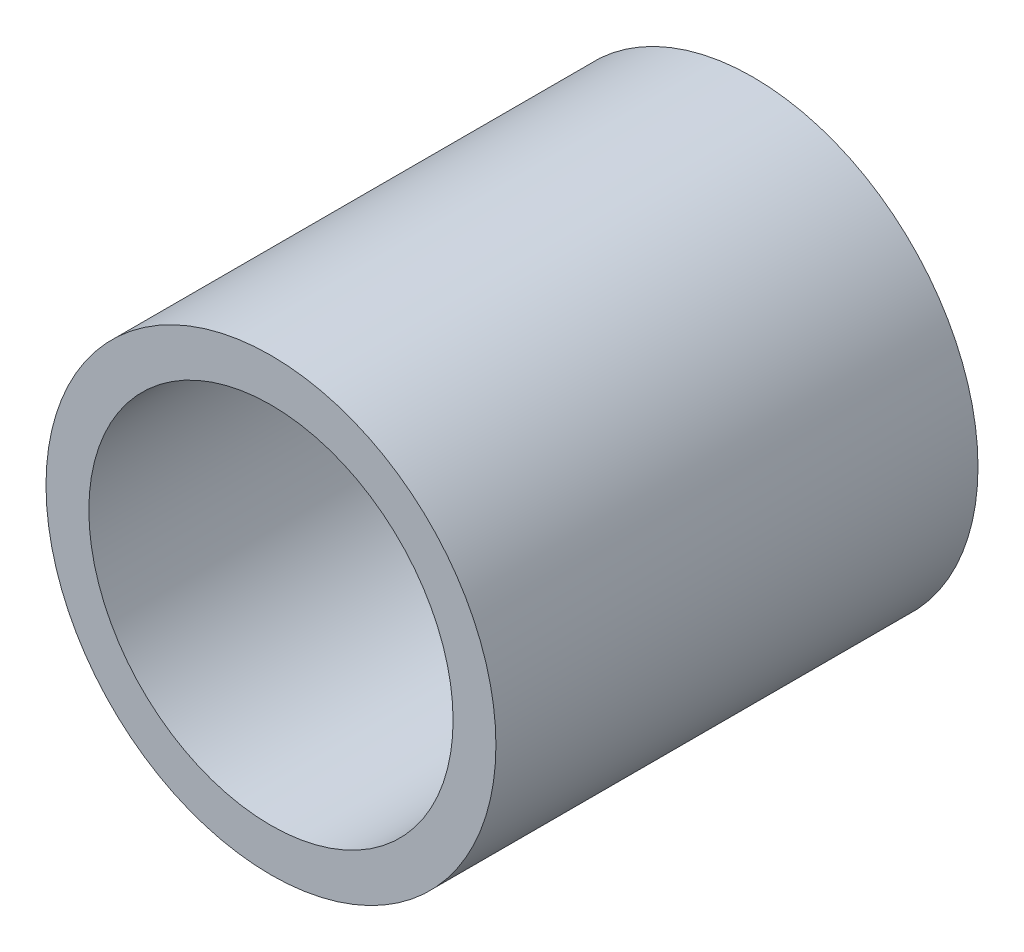
SolidWorks part; units mm, degrees
ref_plane "Front" through (0, 0, 0) normal (0, 0, 1) x (1, 0, 0)
ref_plane "Top" through (0, 0, 0) normal (0, 1, 0) x (1, 0, 0)
ref_plane "Right" through (0, 0, 0) normal (1, 0, 0) x (0, 0, -1)
sketch "Sketch1" plane through (0, 0, 0) normal (0, 0, 1) x (1, 0, 0)
  circle A0 centre (0, 0) radius 17
  circle A1 centre (0, 0) radius 21
  dimension "D1" = 34
  dimension "D2" = 42
extrude "Boss-Extrude1" add sketch "Sketch1" along normal blind 45
